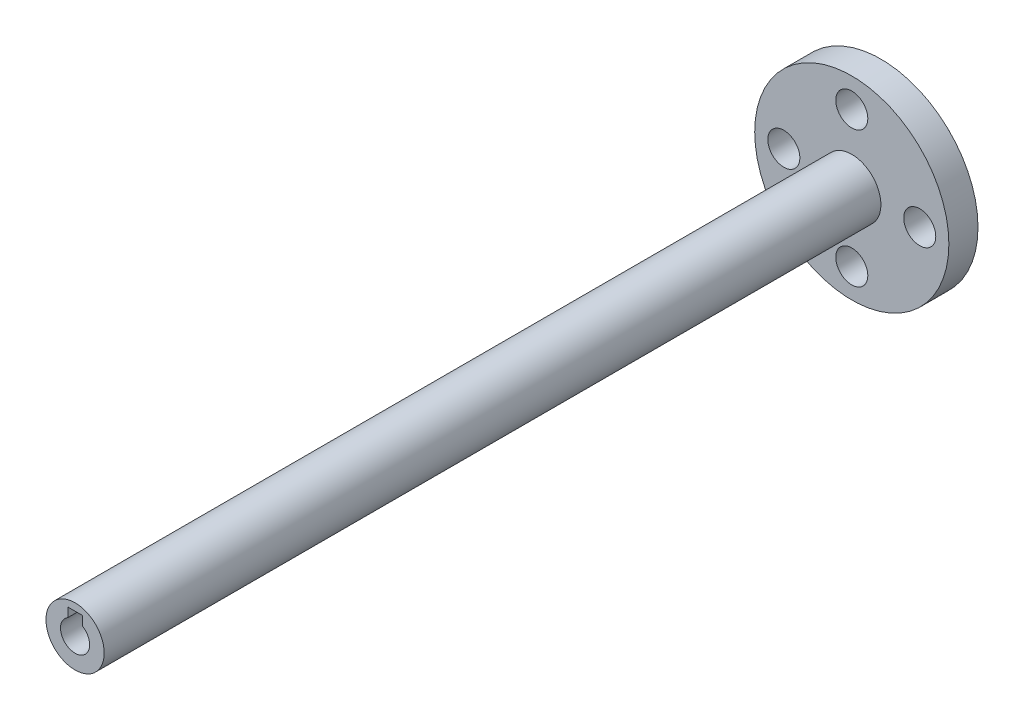
SolidWorks part; units mm, degrees
ref_plane "前视基准面" through (0, 0, 0) normal (0, 0, 1) x (1, 0, 0)
ref_plane "上视基准面" through (0, 0, 0) normal (0, 1, 0) x (1, 0, 0)
ref_plane "右视基准面" through (0, 0, 0) normal (1, 0, 0) x (0, 0, -1)
sketch "草图1" plane through (0, 0, 0) normal (0, 0, 1) x (1, 0, 0)
  line L0 (-10, 0) -> (10, 0) construction
  line L1 (0, 10) -> (0, -10.2805) construction
  circle A0 centre (0, 0) radius 10
  circle A1 centre (0, 7) radius 1.65
  circle A2 centre (7, 0) radius 1.65
  circle A3 centre (0, -7) radius 1.65
  circle A4 centre (-7, 0) radius 1.65
  dimension "D1" = 20
  dimension "D2" = 3.3
  dimension "D3" = 3.3
  dimension "D4" = 3.3
  dimension "D5" = 3.3
  dimension "D6" = 7
  dimension "D7" = 7
  dimension "D8" = 7
  dimension "D9" = 7
extrude "凸台-拉伸1" add sketch "草图1" along normal blind 3
sketch "草图2" plane through (0, 0, 3) normal (0, 0, 1) x (1, 0, 0)
  circle A0 centre (0, 0) radius 3
  dimension "D1" = 6
extrude "凸台-拉伸2" add sketch "草图2" along normal blind 80
sketch "草图3" plane through (0, 0, 83) normal (0, 0, 1) x (1, 0, 0)
  line L0 (0, 0) -> (0, 3) construction
  line L3 (-0.75, 1.299) -> (-0.75, 2.25)
  line L4 (-0.75, 2.25) -> (0.75, 2.25)
  line L5 (0.75, 1.299) -> (0.75, 2.25)
  line L6 (-0.75, 0.75) -> (0.75, 2.25) construction
  line L7 (-0.75, 2.25) -> (0.75, 0.75) construction
  arc A0 (-0.75, 1.299) -> (0.75, 1.299) centre (0, 0) ccw
  circle A1 centre (0, 0) radius 3 construction
  point P3 (0, 1.5)
  dimension "D1" = 3
  dimension "D2" = 1.5
  dimension "D3" = 1.5
extrude "切除-拉伸1" cut sketch "草图3" against normal blind 20
